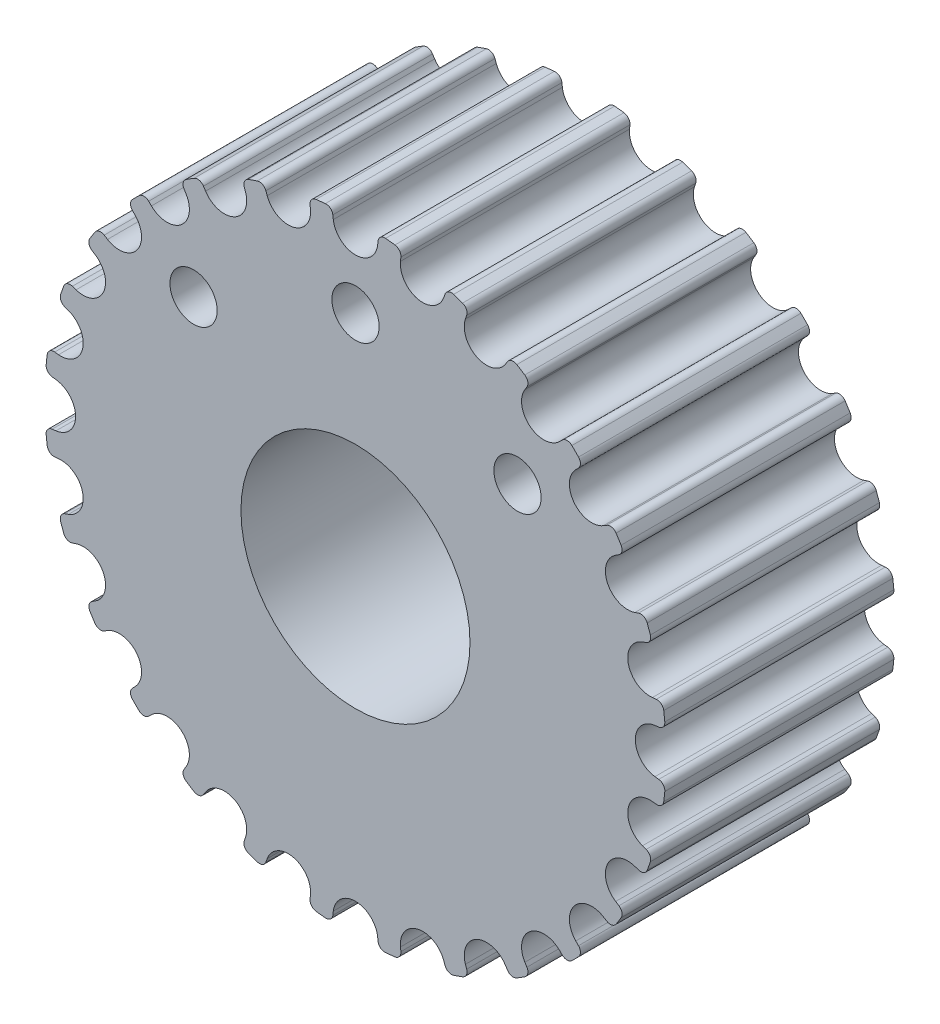
SolidWorks part; units mm, degrees
material "6061 合金"
ref_plane "前视基准面" through (0, 0, 0) normal (0, 0, 1) x (1, 0, 0)
ref_plane "上视基准面" through (0, 0, 0) normal (0, 1, 0) x (1, 0, 0)
ref_plane "右视基准面" through (0, 0, 0) normal (1, 0, 0) x (0, 0, -1)
sketch "草图2" plane through (0, 0, 0) normal (0, 0, 1) x (1, 0, 0)
  line L36 (1.3319, 20.7804) -> (1.2989, 20.5118)
  line L37 (-1.7978, 20.5118) -> (-1.8308, 20.7804)
  line L38 (-3.4222, 20.6011) -> (-3.3946, 20.3319)
  line L39 (-6.4137, 19.6428) -> (-6.5056, 19.8973)
  line L40 (-8.0172, 19.3684) -> (-7.9303, 19.1121)
  line L41 (-10.7204, 17.7684) -> (-10.8667, 17.9962)
  line L42 (-12.2227, 17.1441) -> (-12.081, 16.9135)
  line L43 (-14.5021, 14.9827) -> (-14.6954, 15.1722)
  line L44 (-15.8278, 14.0398) -> (-15.6383, 13.8465)
  line L45 (-17.5691, 11.4254) -> (-17.7997, 11.5671)
  line L46 (-18.6517, 10.2111) -> (-18.424, 10.0648)
  line L47 (-19.7676, 7.2748) -> (-20.024, 7.3616)
  line L48 (-20.5529, 5.85) -> (-20.2983, 5.7581)
  line L49 (-20.9874, 2.739) -> (-21.2567, 2.7666)
  line L50 (-21.436, 1.1752) -> (-21.1673, 1.1423)
  line L51 (-21.1673, -1.9545) -> (-21.436, -1.9875)
  line L52 (-21.2567, -3.5789) -> (-20.9874, -3.5512)
  line L53 (-20.2983, -6.5703) -> (-20.5529, -6.6623)
  line L54 (-20.024, -8.1739) -> (-19.7676, -8.087)
  line L55 (-18.424, -10.8771) -> (-18.6517, -11.0234)
  line L56 (-17.7997, -12.3793) -> (-17.5691, -12.2376)
  line L57 (-15.6383, -14.6588) -> (-15.8278, -14.8521)
  line L58 (-14.6954, -15.9845) -> (-14.5021, -15.795)
  line L59 (-12.081, -17.7258) -> (-12.2227, -17.9564)
  line L60 (-10.8667, -18.8084) -> (-10.7204, -18.5807)
  line L61 (-7.9303, -19.9243) -> (-8.0172, -20.1806)
  line L62 (-6.5056, -20.7096) -> (-6.4137, -20.455)
  line L63 (-3.3946, -21.1441) -> (-3.4222, -21.4133)
  line L64 (-1.8308, -21.5926) -> (-1.7978, -21.324)
  line L65 (1.2989, -21.324) -> (1.3319, -21.5926)
  line L66 (2.9233, -21.4133) -> (2.8957, -21.1441)
  line L67 (5.9148, -20.455) -> (6.0067, -20.7096)
  line L68 (7.5183, -20.1806) -> (7.4314, -19.9243)
  line L69 (10.2215, -18.5807) -> (10.3678, -18.8084)
  line L70 (11.7238, -17.9564) -> (11.5821, -17.7258)
  line L71 (14.0032, -15.795) -> (14.1965, -15.9845)
  line L72 (15.3289, -14.8521) -> (15.1394, -14.6588)
  line L73 (17.0702, -12.2376) -> (17.3008, -12.3793)
  line L74 (18.1528, -11.0234) -> (17.9251, -10.8771)
  line L75 (19.2687, -8.087) -> (19.5251, -8.1739)
  line L76 (20.054, -6.6623) -> (19.7994, -6.5703)
  line L77 (20.4885, -3.5512) -> (20.7578, -3.5789)
  line L78 (20.9371, -1.9875) -> (20.6684, -1.9545)
  line L79 (20.6684, 1.1423) -> (20.9371, 1.1752)
  line L80 (20.7578, 2.7666) -> (20.4885, 2.739)
  line L81 (19.7994, 5.7581) -> (20.054, 5.85)
  line L82 (19.5251, 7.3616) -> (19.2687, 7.2748)
  line L83 (17.9251, 10.0648) -> (18.1528, 10.2111)
  line L84 (17.3008, 11.5671) -> (17.0702, 11.4254)
  line L85 (15.1394, 13.8465) -> (15.3289, 14.0398)
  line L86 (14.1965, 15.1722) -> (14.0032, 14.9827)
  line L87 (11.5821, 16.9135) -> (11.7238, 17.1441)
  line L88 (10.3678, 17.9962) -> (10.2215, 17.7684)
  line L89 (7.4314, 19.1121) -> (7.5183, 19.3684)
  line L90 (6.0067, 19.8973) -> (5.9148, 19.6428)
  line L91 (2.8957, 20.3319) -> (2.9233, 20.6011)
  circle A72 centre (-0.2458, -0.3677) radius 12 construction
  circle A73 centre (-0.2458, -0.3677) radius 10.5
  arc A74 (2.9233, 20.6011) -> (2.5067, 21.1262) centre (2.4458, 20.6501) ccw
  arc A75 (2.5067, 21.1262) -> (1.8549, 21.1996) centre (-0.2495, -0.4061) ccw
  arc A76 (1.8549, 21.1996) -> (1.3319, 20.7804) centre (1.8083, 20.7219) ccw
  arc A77 (-1.7978, 20.5118) -> (1.2989, 20.5118) centre (-0.2495, 20.7019) ccw
  arc A78 (-1.8308, 20.7804) -> (-2.3538, 21.1996) centre (-2.3072, 20.7219) ccw
  arc A79 (-2.3538, 21.1996) -> (-3.0056, 21.1262) centre (-0.2495, -0.4061) ccw
  arc A80 (-3.0056, 21.1262) -> (-3.4222, 20.6011) centre (-2.9447, 20.6501) ccw
  arc A81 (-6.4137, 19.6428) -> (-3.3946, 20.3319) centre (-4.9464, 20.1727) ccw
  arc A82 (-6.5056, 19.8973) -> (-7.1087, 20.1897) centre (-6.9571, 19.7343) ccw
  arc A83 (-7.1087, 20.1897) -> (-7.7279, 19.973) centre (-0.2495, -0.4061) ccw
  arc A84 (-7.7279, 19.973) -> (-8.0172, 19.3684) centre (-7.5626, 19.5224) ccw
  arc A85 (-10.7204, 17.7684) -> (-7.9303, 19.1121) centre (-9.4079, 18.6115) ccw
  arc A86 (-10.8667, 17.9962) -> (-11.5198, 18.147) centre (-11.2706, 17.7367) ccw
  arc A87 (-11.5198, 18.147) -> (-12.0752, 17.798) centre (-0.2495, -0.4061) ccw
  arc A88 (-12.0752, 17.798) -> (-12.2227, 17.1441) centre (-11.8137, 17.3954) ccw
  arc A89 (-14.5021, 14.9827) -> (-12.081, 16.9135) centre (-13.4101, 16.0968) ccw
  arc A90 (-14.6954, 15.1722) -> (-15.3656, 15.1739) centre (-15.0314, 14.8294) ccw
  arc A91 (-15.3656, 15.1739) -> (-15.8295, 14.7101) centre (-0.2495, -0.4061) ccw
  arc A92 (-15.8295, 14.7101) -> (-15.8278, 14.0398) centre (-15.485, 14.3758) ccw
  arc A93 (-17.5691, 11.4254) -> (-15.6383, 13.8465) centre (-16.7524, 12.7545) ccw
  arc A94 (-17.7997, 11.5671) -> (-18.4535, 11.4196) centre (-18.051, 11.1582) ccw
  arc A95 (-18.4535, 11.4196) -> (-18.8026, 10.8642) centre (-0.2495, -0.4061) ccw
  arc A96 (-18.8026, 10.8642) -> (-18.6517, 10.2111) centre (-18.3923, 10.615) ccw
  arc A97 (-19.7676, 7.2748) -> (-18.424, 10.0648) centre (-19.2671, 8.7523) ccw
  arc A98 (-20.024, 7.3616) -> (-20.6286, 7.0724) centre (-20.178, 6.907) ccw
  arc A99 (-20.6286, 7.0724) -> (-20.8453, 6.4532) centre (-0.2495, -0.4061) ccw
  arc A100 (-20.8453, 6.4532) -> (-20.5529, 5.85) centre (-20.3899, 6.3015) ccw
  arc A101 (-20.9874, 2.739) -> (-20.2983, 5.7581) centre (-20.8282, 4.2909) ccw
  arc A102 (-21.2567, 2.7666) -> (-21.7818, 2.3501) centre (-21.3057, 2.2891) ccw
  arc A103 (-21.7818, 2.3501) -> (-21.8552, 1.6982) centre (-0.2495, -0.4061) ccw
  arc A104 (-21.8552, 1.6982) -> (-21.436, 1.1752) centre (-21.3775, 1.6517) ccw
  arc A105 (-21.1673, -1.9545) -> (-21.1673, 1.1423) centre (-21.3575, -0.4061) ccw
  arc A106 (-21.436, -1.9875) -> (-21.8552, -2.5104) centre (-21.3775, -2.4639) ccw
  arc A107 (-21.8552, -2.5104) -> (-21.7818, -3.1623) centre (-0.2495, -0.4061) ccw
  arc A108 (-21.7818, -3.1623) -> (-21.2567, -3.5789) centre (-21.3057, -3.1014) ccw
  arc A109 (-20.2983, -6.5703) -> (-20.9874, -3.5512) centre (-20.8282, -5.1031) ccw
  arc A110 (-20.5529, -6.6623) -> (-20.8453, -7.2654) centre (-20.3899, -7.1137) ccw
  arc A111 (-20.8453, -7.2654) -> (-20.6286, -7.8846) centre (-0.2495, -0.4061) ccw
  arc A112 (-20.6286, -7.8846) -> (-20.024, -8.1739) centre (-20.178, -7.7192) ccw
  arc A113 (-18.424, -10.8771) -> (-19.7676, -8.087) centre (-19.2671, -9.5645) ccw
  arc A114 (-18.6517, -11.0234) -> (-18.8026, -11.6764) centre (-18.3923, -11.4272) ccw
  arc A115 (-18.8026, -11.6764) -> (-18.4535, -12.2319) centre (-0.2495, -0.4061) ccw
  arc A116 (-18.4535, -12.2319) -> (-17.7997, -12.3793) centre (-18.051, -11.9704) ccw
  arc A117 (-15.6383, -14.6588) -> (-17.5691, -12.2376) centre (-16.7524, -13.5667) ccw
  arc A118 (-15.8278, -14.8521) -> (-15.8295, -15.5223) centre (-15.485, -15.1881) ccw
  arc A119 (-15.8295, -15.5223) -> (-15.3656, -15.9862) centre (-0.2495, -0.4061) ccw
  arc A120 (-15.3656, -15.9862) -> (-14.6954, -15.9845) centre (-15.0314, -15.6417) ccw
  arc A121 (-12.081, -17.7258) -> (-14.5021, -15.795) centre (-13.4101, -16.909) ccw
  arc A122 (-12.2227, -17.9564) -> (-12.0752, -18.6102) centre (-11.8137, -18.2077) ccw
  arc A123 (-12.0752, -18.6102) -> (-11.5198, -18.9592) centre (-0.2495, -0.4061) ccw
  arc A124 (-11.5198, -18.9592) -> (-10.8667, -18.8084) centre (-11.2706, -18.549) ccw
  arc A125 (-7.9303, -19.9243) -> (-10.7204, -18.5807) centre (-9.4079, -19.4238) ccw
  arc A126 (-8.0172, -20.1806) -> (-7.7279, -20.7853) centre (-7.5626, -20.3347) ccw
  arc A127 (-7.7279, -20.7853) -> (-7.1087, -21.0019) centre (-0.2495, -0.4061) ccw
  arc A128 (-7.1087, -21.0019) -> (-6.5056, -20.7096) centre (-6.9571, -20.5465) ccw
  arc A129 (-3.3946, -21.1441) -> (-6.4137, -20.455) centre (-4.9464, -20.9849) ccw
  arc A130 (-3.4222, -21.4133) -> (-3.0056, -21.9384) centre (-2.9447, -21.4623) ccw
  arc A131 (-3.0056, -21.9384) -> (-2.3538, -22.0119) centre (-0.2495, -0.4061) ccw
  arc A132 (-2.3538, -22.0119) -> (-1.8308, -21.5926) centre (-2.3072, -21.5341) ccw
  arc A133 (1.2989, -21.324) -> (-1.7978, -21.324) centre (-0.2495, -21.5141) ccw
  arc A134 (1.3319, -21.5926) -> (1.8549, -22.0119) centre (1.8083, -21.5341) ccw
  arc A135 (1.8549, -22.0119) -> (2.5067, -21.9384) centre (-0.2495, -0.4061) ccw
  arc A136 (2.5067, -21.9384) -> (2.9233, -21.4133) centre (2.4458, -21.4623) ccw
  arc A137 (5.9148, -20.455) -> (2.8957, -21.1441) centre (4.4475, -20.9849) ccw
  arc A138 (6.0067, -20.7096) -> (6.6098, -21.0019) centre (6.4582, -20.5465) ccw
  arc A139 (6.6098, -21.0019) -> (7.229, -20.7853) centre (-0.2495, -0.4061) ccw
  arc A140 (7.229, -20.7853) -> (7.5183, -20.1806) centre (7.0637, -20.3347) ccw
  arc A141 (10.2215, -18.5807) -> (7.4314, -19.9243) centre (8.909, -19.4238) ccw
  arc A142 (10.3678, -18.8084) -> (11.0209, -18.9592) centre (10.7716, -18.549) ccw
  arc A143 (11.0209, -18.9592) -> (11.5763, -18.6102) centre (-0.2495, -0.4061) ccw
  arc A144 (11.5763, -18.6102) -> (11.7238, -17.9564) centre (11.3148, -18.2077) ccw
  arc A145 (14.0032, -15.795) -> (11.5821, -17.7258) centre (12.9112, -16.909) ccw
  arc A146 (14.1965, -15.9845) -> (14.8667, -15.9862) centre (14.5325, -15.6417) ccw
  arc A147 (14.8667, -15.9862) -> (15.3306, -15.5223) centre (-0.2495, -0.4061) ccw
  arc A148 (15.3306, -15.5223) -> (15.3289, -14.8521) centre (14.9861, -15.1881) ccw
  arc A149 (17.0702, -12.2376) -> (15.1394, -14.6588) centre (16.2534, -13.5667) ccw
  arc A150 (17.3008, -12.3793) -> (17.9546, -12.2319) centre (17.5521, -11.9704) ccw
  arc A151 (17.9546, -12.2319) -> (18.3036, -11.6764) centre (-0.2495, -0.4061) ccw
  arc A152 (18.3036, -11.6764) -> (18.1528, -11.0234) centre (17.8934, -11.4272) ccw
  arc A153 (19.2687, -8.087) -> (17.9251, -10.8771) centre (18.7682, -9.5645) ccw
  arc A154 (19.5251, -8.1739) -> (20.1297, -7.8846) centre (19.6791, -7.7192) ccw
  arc A155 (20.1297, -7.8846) -> (20.3464, -7.2654) centre (-0.2495, -0.4061) ccw
  arc A156 (20.3464, -7.2654) -> (20.054, -6.6623) centre (19.891, -7.1137) ccw
  arc A157 (20.4885, -3.5512) -> (19.7994, -6.5703) centre (20.3293, -5.1031) ccw
  arc A158 (20.7578, -3.5789) -> (21.2829, -3.1623) centre (20.8067, -3.1014) ccw
  arc A159 (21.2829, -3.1623) -> (21.3563, -2.5104) centre (-0.2495, -0.4061) ccw
  arc A160 (21.3563, -2.5104) -> (20.9371, -1.9875) centre (20.8786, -2.4639) ccw
  arc A161 (20.6684, 1.1423) -> (20.6684, -1.9545) centre (20.8585, -0.4061) ccw
  arc A162 (20.9371, 1.1752) -> (21.3563, 1.6982) centre (20.8786, 1.6517) ccw
  arc A163 (21.3563, 1.6982) -> (21.2829, 2.3501) centre (-0.2495, -0.4061) ccw
  arc A164 (21.2829, 2.3501) -> (20.7578, 2.7666) centre (20.8067, 2.2891) ccw
  arc A165 (19.7994, 5.7581) -> (20.4885, 2.739) centre (20.3293, 4.2909) ccw
  arc A166 (20.054, 5.85) -> (20.3464, 6.4532) centre (19.891, 6.3015) ccw
  arc A167 (20.3464, 6.4532) -> (20.1297, 7.0724) centre (-0.2495, -0.4061) ccw
  arc A168 (20.1297, 7.0724) -> (19.5251, 7.3616) centre (19.6791, 6.907) ccw
  arc A169 (17.9251, 10.0648) -> (19.2687, 7.2748) centre (18.7682, 8.7523) ccw
  arc A170 (18.1528, 10.2111) -> (18.3036, 10.8642) centre (17.8934, 10.615) ccw
  arc A171 (18.3036, 10.8642) -> (17.9546, 11.4196) centre (-0.2495, -0.4061) ccw
  arc A172 (17.9546, 11.4196) -> (17.3008, 11.5671) centre (17.5521, 11.1582) ccw
  arc A173 (15.1394, 13.8465) -> (17.0702, 11.4254) centre (16.2534, 12.7545) ccw
  arc A174 (15.3289, 14.0398) -> (15.3306, 14.7101) centre (14.9861, 14.3758) ccw
  arc A175 (15.3306, 14.7101) -> (14.8667, 15.1739) centre (-0.2495, -0.4061) ccw
  arc A176 (14.8667, 15.1739) -> (14.1965, 15.1722) centre (14.5325, 14.8294) ccw
  arc A177 (11.5821, 16.9135) -> (14.0032, 14.9827) centre (12.9112, 16.0968) ccw
  arc A178 (11.7238, 17.1441) -> (11.5763, 17.798) centre (11.3148, 17.3954) ccw
  arc A179 (11.5763, 17.798) -> (11.0209, 18.147) centre (-0.2495, -0.4061) ccw
  arc A180 (11.0209, 18.147) -> (10.3678, 17.9962) centre (10.7716, 17.7367) ccw
  arc A181 (7.4314, 19.1121) -> (10.2215, 17.7684) centre (8.909, 18.6115) ccw
  arc A182 (7.5183, 19.3684) -> (7.229, 19.973) centre (7.0637, 19.5224) ccw
  arc A183 (7.229, 19.973) -> (6.6098, 20.1897) centre (-0.2495, -0.4061) ccw
  arc A184 (6.6098, 20.1897) -> (6.0067, 19.8973) centre (6.4582, 19.7343) ccw
  arc A185 (2.8957, 20.3319) -> (5.9148, 19.6428) centre (4.4475, 20.1727) ccw
  dimension "D1" = 21
extrude "凸台-拉伸1" add sketch "草图2" along normal blind 16
move or copy body "实体-移动/复制1" bodies to move or copy 106 copy no translate (-21.7751, 0, 0) parameters "D1"=21.7751, "D2"=0, "D3"=0
sketch "草图12" plane through (0, 0, 16) normal (0, 0, 1) x (1, 0, 0)
  circle A0 centre (-22.0209, -0.3677) radius 10.5 construction
  circle A1 centre (-22.0209, -0.3677) radius 10.5
  circle A2 centre (-22.0246, -0.3096) radius 11.5
  circle A3 centre (-22.0246, -0.3096) radius 13
  circle A4 centre (-22.0209, -0.3677) radius 16
  point P7 (-6.0209, -0.3677)
  point P10 (-10.7072, -11.6815)
  point P11 (-22.0209, -16.3677)
  point P12 (-33.3346, -11.6815)
  point P13 (-38.0209, -0.3677)
  point P14 (-33.3346, 10.946)
  point P15 (-22.0209, 15.6323)
  point P16 (-10.7072, 10.946)
  point P17 (-22.0209, -0.3677)
  dimension "D1" = 23
  dimension "D2" = 26
  dimension "D3" = 32
  dimension "D4" = 8
extrude "凸台-拉伸2" add sketch "草图12" along normal blind 4 and the other way blind 18 contours A3 A2
sketch "草图14" plane through (0, 0, 16) normal (0, 0, 1) x (1, 0, 0)
  circle A0 centre (-22.0209, -0.3677) radius 10.5 construction
  circle A1 centre (-22.0246, -0.3096) radius 11.5
  circle A2 centre (-22.0246, -0.3096) radius 11.5
  circle A3 centre (-22.0209, -0.3677) radius 10.5
  dimension "D1" = 0
extrude "切除-拉伸1" cut sketch "草图14" against normal blind 1.1
sketch "草图15" plane through (0, 0, 16) normal (0, 0, 1) x (1, 0, 0)
  circle A0 centre (-22.0209, -0.3677) radius 16 construction
  circle A1 centre (-22.0209, -0.3677) radius 16 construction
  circle A2 centre (-22.0209, 15.6323) radius 4.05
  circle A3 centre (-10.7072, 10.946) radius 4.05
  circle A4 centre (-6.0209, -0.3677) radius 4.05 [skipped]
  circle A8 centre (-38.0209, -0.3677) radius 4.05 [skipped]
  circle A9 centre (-33.3346, 10.946) radius 4.05
  circle A10 centre (-10.7072, -11.6815) radius 4.05 [skipped]
  circle A11 centre (-33.3346, -11.6815) radius 4.05 [skipped]
  circle A12 centre (-22.0209, -16.3677) radius 4.05 [skipped]
  point P0 (-33.3346, -11.6815)
  point P2 (-22.0209, -16.3677)
  point P4 (-10.7072, -11.6815)
  point P6 (-10.7072, 10.946)
  point P8 (-22.0209, 15.6323)
  point P10 (-33.3346, 10.946)
  point P34 (-22.0209, -0.3677)
  dimension "D1" = 8.1
  dimension "D2" = 8
sketch "草图16" plane through (0, 0, 0) normal (0, 0, -1) x (-1, 0, 0)
  circle A0 centre (22.0209, -0.3677) radius 10.5 construction
  circle A1 centre (22.0246, -0.3096) radius 11.5
  circle A2 centre (22.0246, -0.3096) radius 11.5
  circle A3 centre (22.0209, -0.3677) radius 10.5
  dimension "D1" = 0
sketch "草图18" plane through (0, 0, 0) normal (0, 0, -1) x (-1, 0, 0)
  line L0 (22.0209, -0.3677) -> (22.0209, 21.2599) construction
  line L1 (22.0209, -0.3677) -> (3.1451, 18.5081) construction
  line L2 (22.0209, -0.3677) -> (38.7709, 16.3822) construction
  circle A0 centre (22.0209, -0.3677) radius 16 construction
  circle A1 centre (10.7072, 10.946) radius 1.65
  circle A3 centre (22.0209, 15.6323) radius 1.65
  circle A4 centre (33.3346, 10.946) radius 1.65
  circle A5 centre (22.0209, -0.3677) radius 12.9417 construction
  point P14 (33.3346, 10.946)
  dimension "D1" = 32
  dimension "D3" = 3.3
  dimension "D4" = 3.3
  dimension "D6" = 3.3
  dimension "D2" = 45
  dimension "D5" = 45
extrude "切除-拉伸5" cut sketch "草图16" against normal blind 1.1
sketch "草图20" plane through (0, 0, 20) normal (0, 0, 1) x (1, 0, 0)
  circle A0 centre (-22.0246, -0.3096) radius 11.9673
extrude "凸台-拉伸3" add sketch "草图20" against normal up to surface (22 mm away) up to face at (-10.5246, -0.3096, -2)
sketch "草图21" plane through (0, 0, -2) normal (0, 0, -1) x (-1, 0, 0)
  circle A0 centre (22.0246, -0.3096) radius 13
extrude "凸台-拉伸4" add sketch "草图21" along normal blind 1
sketch "草图22" plane through (0, 0, -3) normal (0, 0, -1) x (-1, 0, 0)
  circle A0 centre (22.0246, -0.3096) radius 11.5
  circle A1 centre (22.0246, -0.3096) radius 8.5
  dimension "D1" = 23
  dimension "D2" = 17
extrude "切除-拉伸6" cut sketch "草图22" against normal blind 4.1
sketch "草图23" plane through (0, 0, -3) normal (0, 0, -1) x (-1, 0, 0)
  circle A0 centre (22.0246, -0.3096) radius 8.5
extrude "切除-拉伸7" cut sketch "草图23" against normal blind 33.1
sketch "草图24" plane through (0, 0, 20) normal (0, 0, 1) x (1, 0, 0)
  circle A0 centre (-22.0246, -0.3096) radius 11.5
  dimension "D1" = 23
extrude "切除-拉伸8" cut sketch "草图24" against normal blind 4.1
sketch "草图25" plane through (0, 0, -3) normal (0, 0, -1) x (-1, 0, 0)
  circle A0 centre (22.0246, -0.3096) radius 14.3512
extrude "切除-拉伸9" cut sketch "草图25" against normal blind 35
sketch "草图26" plane through (0, 0, 0) normal (0, 0, -1) x (-1, 0, 0)
  circle A0 centre (22.0246, -0.3096) radius 14.8679
extrude "凸台-拉伸5" add sketch "草图26" against normal up to surface (16 mm away) up to face at (-7.6733, -0.3096, 16)
sketch "草图27" plane through (0, 0, 0) normal (0, 0, -1) x (-1, 0, 0)
  circle A0 centre (22.0246, -0.3096) radius 8
  dimension "D1" = 16
extrude "切除-拉伸10" cut sketch "草图27" against normal blind 20
sketch "草图30" plane through (0, 0, 0) normal (0, 0, -1) x (-1, 0, 0)
  circle A0 centre (22.0246, -0.3096) radius 10.5
  circle A1 centre (22.0246, -0.3096) radius 12.75
  dimension "D1" = 21
  dimension "D2" = 25.5
extrude "凸台-拉伸6" add sketch "草图30" along normal blind 3.6 contours A1 | A0
sketch "草图31" plane through (0, 0, 0) normal (0, 0, -1) x (-1, 0, 0)
  circle A1 centre (22.0246, -0.3096) radius 10.5
ref_plane "基准面2" through (0, 0, 8) normal (0, 0, -1) x (-1, 0, 0)
extrude "切除-拉伸15" cut sketch "草图18" against normal blind 25
